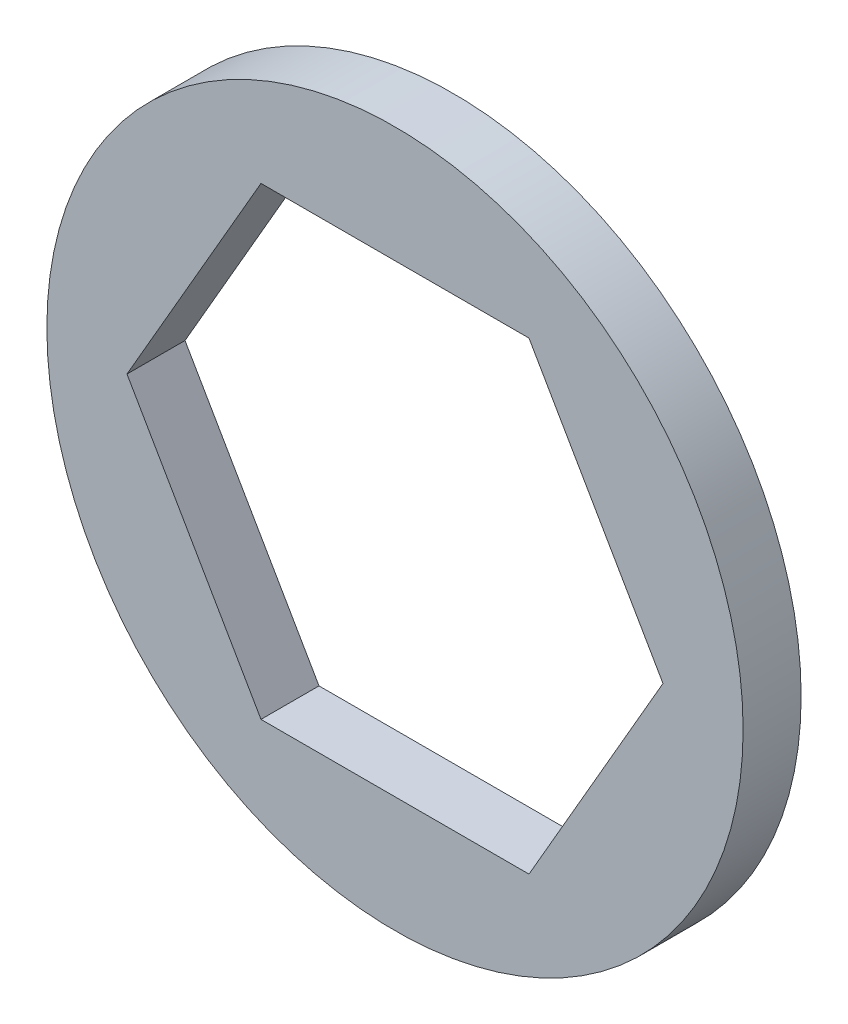
SolidWorks part; units mm, degrees
material "PET"
ref_plane "Front Plane" through (0, 0, 0) normal (0, 0, 1) x (1, 0, 0)
ref_plane "Top Plane" through (0, 0, 0) normal (0, 1, 0) x (1, 0, 0)
ref_plane "Right Plane" through (0, 0, 0) normal (1, 0, 0) x (0, 0, -1)
sketch "Sketch1" plane through (0, 0, 0) normal (0, 0, 1) x (1, 0, 0)
  line L1 (7.3323, 0) -> (3.6662, 6.35)
  line L2 (3.6662, 6.35) -> (-3.6662, 6.35)
  line L3 (-3.6662, 6.35) -> (-7.3323, 0)
  line L4 (-7.3323, 0) -> (-3.6662, -6.35)
  line L5 (-3.6662, -6.35) -> (3.6662, -6.35)
  line L6 (3.6662, -6.35) -> (7.3323, 0)
  circle A1 centre (0, 0) radius 6.35 construction
  circle A2 centre (0, 0) radius 9.525
  dimension "D1" = 12.7
  dimension "D2" = 19.05
extrude "Boss-Extrude1" add sketch "Sketch1" along normal blind 1.5875 contours L5 L6 L1 L2 L3 L4 | A2
